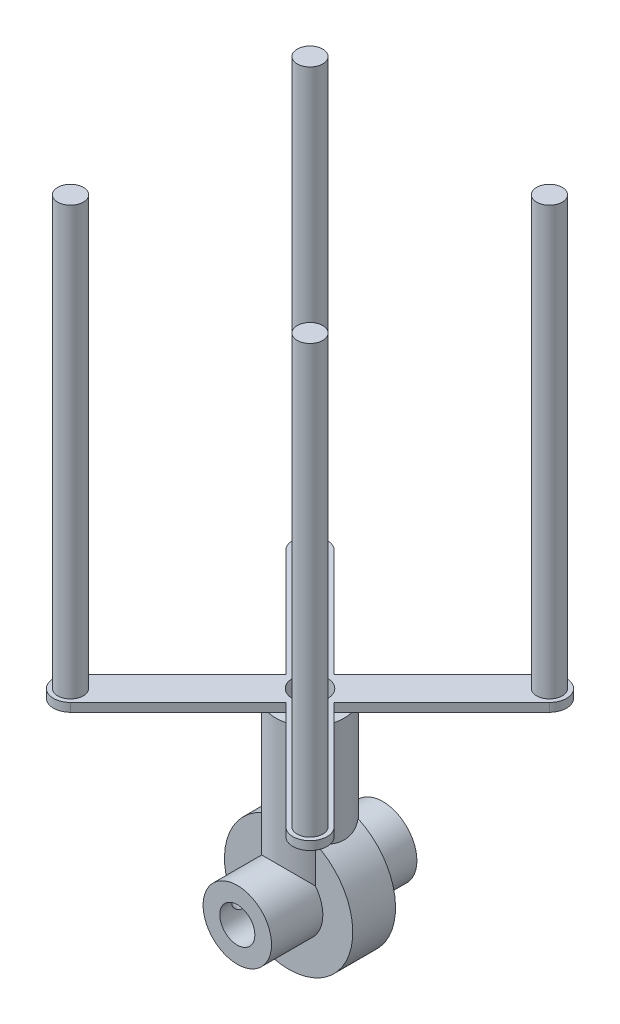
SolidWorks part; units mm, degrees
ref_plane "Front Plane" through (0, 0, 0) normal (0, 0, 1) x (1, 0, 0)
ref_plane "Top Plane" through (0, 0, 0) normal (0, 1, 0) x (1, 0, 0)
ref_plane "Right Plane" through (0, 0, 0) normal (1, 0, 0) x (0, 0, -1)
sketch "Sketch1" plane through (0, 0, 0) normal (0, 0, 1) x (1, 0, 0)
  circle A0 centre (102.3412, 36.4161) radius 7.5
  circle A1 centre (102.3412, 36.4161) radius 2.05
extrude "Boss-Extrude1" add sketch "Sketch1" along normal blind 2.5
sketch "Sketch2" plane through (0, 0, 2.5) normal (0, 0, 1) x (1, 0, 0)
  circle A0 centre (102.3412, 36.4161) radius 2.05
  circle A1 centre (102.3412, 36.4161) radius 4
extrude "Boss-Extrude2" add sketch "Sketch2" along normal blind 6
sketch "Sketch7" plane through (0, 0, 0) normal (0, 0, -1) x (-1, 0, 0)
  line L1 (-106.3412, 36.4161) -> (-102.3412, 36.4161)
  line L2 (-106.3412, 36.4161) -> (-106.3412, 55.1033)
  line L3 (-106.3412, 55.1033) -> (-102.3412, 55.1033)
  line L4 (-102.3412, 36.4161) -> (-102.3412, 55.1033)
revolve "Revolve7" add sketch "Sketch7" angle 180 about L4
sketch "Sketch8" plane through (0, 0, 0) normal (0, 0, -1) x (-1, 0, 0)
  line L0 (-104.3912, 36.4161) -> (-100.2912, 36.4161) construction
  line L1 (-102.3412, 36.4161) -> (-104.3912, 36.4161)
  line L2 (-102.3412, 36.4161) -> (-102.3412, 55.1033)
  line L3 (-102.3412, 55.1033) -> (-104.3912, 55.1033)
  line L4 (-104.3912, 36.4161) -> (-104.3912, 55.1033)
  line L5 (-98.3412, 55.1033) -> (-106.3412, 55.1033) construction
revolve "Cut-Revolve2" cut sketch "Sketch8" angle 360 about L2
sketch "Sketch9" plane through (0, 0, 0) normal (0, 0, -1) x (-1, 0, 0)
  circle A0 centre (-102.3412, 36.4161) radius 2.05
extrude "Cut-Extrude1" cut sketch "Sketch9" against normal blind 5
mirror "Mirror1" about plane through (102.3412, 36.4161, 0) normal (0, 0, 1) of "Cut-Extrude1", "Revolve7", "Boss-Extrude2", "Boss-Extrude1", "Cut-Revolve2"
sketch "Sketch10" plane through (0, 55.1033, 0) normal (0, 1, 0) x (1, 0, 0)
  line L0 (102.3412, 0) -> (88.3412, 14) construction
  line L1 (121.3412, -19) -> (83.3412, -19) construction
  line L2 (121.3412, -19) -> (121.3412, 19) construction
  line L3 (121.3412, 19) -> (83.3412, 19) construction
  line L4 (83.3412, -19) -> (83.3412, 19) construction
  line L5 (121.3412, -19) -> (83.3412, 19) construction
  line L6 (121.3412, 19) -> (83.3412, -19) construction
  line L11 (102.3412, 0) -> (116.3412, 14) construction
  line L14 (102.3412, 0) -> (116.3412, -14) construction
  line L17 (102.3412, 0) -> (88.3412, -14) construction
  line L20 (102.3412, 2.8284) -> (89.7554, 15.4142)
  line L21 (105.1696, 0) -> (117.7554, -12.5858)
  line L22 (105.1696, 0) -> (117.7554, 12.5858)
  line L23 (102.3412, -2.8284) -> (89.7554, -15.4142)
  line L24 (102.3412, -2.8284) -> (114.927, -15.4142)
  line L25 (99.5128, 0) -> (86.927, 12.5858)
  line L26 (99.5128, 0) -> (86.927, -12.5858)
  line L27 (102.3412, 2.8284) -> (114.927, 15.4142)
  arc A4 (89.7554, 15.4142) -> (86.927, 12.5858) centre (88.3412, 14) ccw
  arc A6 (117.7554, 12.5858) -> (114.927, 15.4142) centre (116.3412, 14) ccw
  arc A8 (114.927, -15.4142) -> (117.7554, -12.5858) centre (116.3412, -14) ccw
  arc A10 (86.927, -12.5858) -> (89.7554, -15.4142) centre (88.3412, -14) ccw
  circle A11 centre (102.3412, 0) radius 2.05
  point P0 (102.3412, 0)
  point P8 (95.3412, 7)
  point P18 (109.3412, 7)
  point P25 (109.3412, -7)
  point P32 (95.3412, -7)
  point P38 (102.3412, 0)
  dimension "D1" = 38
  dimension "D2" = 38
  dimension "D3" = 5
  dimension "D4" = 5
extrude "Boss-Extrude3" add sketch "Sketch10" along normal blind 1
sketch "Sketch11" plane through (0, 56.1033, 0) normal (0, 1, 0) x (1, 0, 0)
  circle A4 centre (88.3412, 14) radius 1.5
  circle A5 centre (116.3412, 14) radius 1.5
  circle A6 centre (116.3412, -14) radius 1.5
  circle A7 centre (88.3412, -14) radius 1.5
  point P11 (102.3412, 0)
extrude "Boss-Extrude4" add sketch "Sketch11" along normal blind 50
hole_wizard "M3x0.5 Tapped Hole1" positions "3DSketch1" profile "Sketch12" tap size "M3x0.5" standard "ANSI Metric"
sketch3d "3DSketch1"
  point P0 (98.588, 37.7993, 5.9237)
  point P2 (98.537, 37.6524, -5.5187)
cosmetic thread "Hole Thread1" parameters "D2"=3
cosmetic thread "Hole Thread2" parameters "D2"=3
sketch "Sketch12" plane through (98.588, 37.7993, 5.9237) normal (0, 0, 1) x (-0.3458, -0.9383, 0)
  line L0 (0, 0) -> (0, 1.95)
  line L1 (0, 1.95) -> (1.25, 1.95)
  line L2 (1.25, 1.95) -> (1.25, 0)
  line L5 (1.25, 0) -> (0, 0)
  line L11 (0, -6.35) -> (0, 107.95) construction
  dimension "Thru Tap Drill Dia." = 2.5
  dimension "Thru Tap Drill Depth" = 1.95
